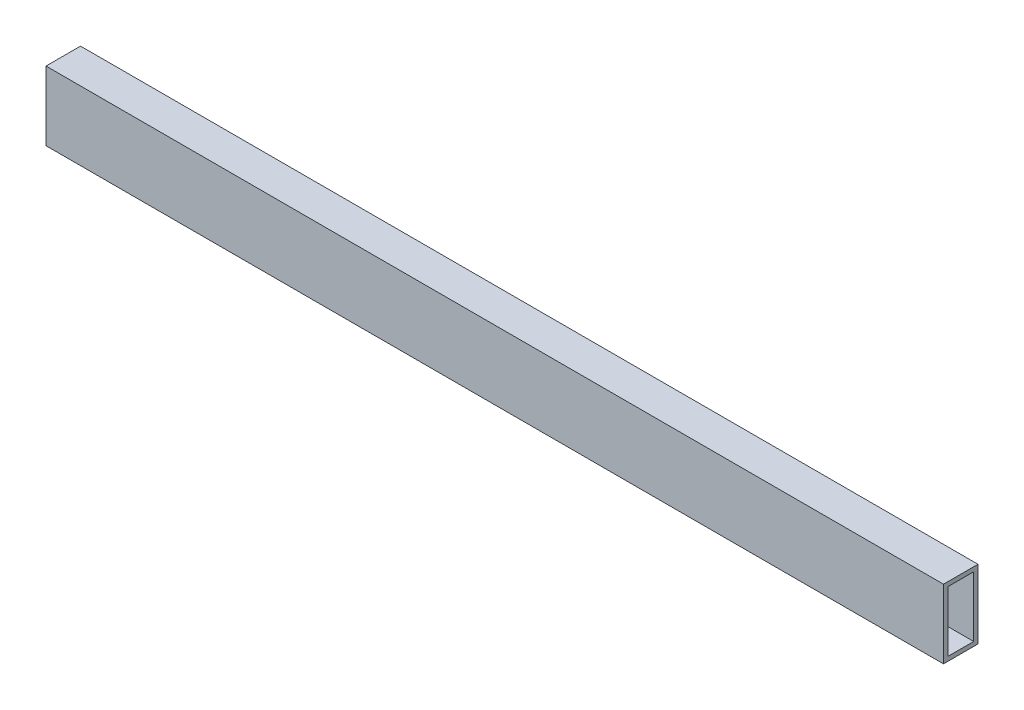
SolidWorks part; units mm, degrees
material "6061-T6 (SS)"
ref_plane "Front Plane" through (0, 0, 0) normal (0, 0, 1) x (1, 0, 0)
ref_plane "Top Plane" through (0, 0, 0) normal (0, 1, 0) x (1, 0, 0)
ref_plane "Right Plane" through (0, 0, 0) normal (1, 0, 0) x (0, 0, -1)
sketch "Sketch1" plane through (0, 0, 0) normal (1, 0, 0) x (0, 0, -1)
  line L0 (-355.6, 25.4) -> (-381, 25.4) construction
  line L1 (-381, -25.4) -> (-381, 25.4) construction
  line L2 (-355.6, -25.4) -> (-381, -25.4) construction
  line L3 (-355.6, -25.4) -> (-355.6, 25.4) construction
  line L4 (-355.6, 25.4) -> (-381, 25.4)
  line L5 (-381, -25.4) -> (-381, 25.4)
  line L6 (-355.6, -25.4) -> (-381, -25.4)
  line L7 (-355.6, -25.4) -> (-355.6, 25.4)
  line L8 (-358.775, 22.225) -> (-377.825, 22.225)
  line L9 (-377.825, -22.225) -> (-377.825, 22.225)
  line L10 (-358.775, -22.225) -> (-377.825, -22.225)
  line L11 (-358.775, -22.225) -> (-358.775, 22.225)
  dimension "D1" = 3.175
extrude "Boss-Extrude1" add sketch "Sketch1" along normal up to vertex (330.2 mm away)
ref_plane "Plane1" through (330.2, 25.4, 355.6) normal (-1, 0, 0) x (0, 0, 1)
sketch "Sketch3" plane through (0, 0, 0) normal (0, 1, 0) x (1, 0, 0)
  line L0 (266.7, -381) -> (221.678, -335.978) construction
  line L1 (266.7, -381) -> (221.678, -335.978)
  line L4 (221.678, -335.978) -> (266.7, -335.978)
  line L5 (266.7, -381) -> (266.7, 0) construction
  line L6 (266.7, -335.978) -> (266.7, -381)
extrude "Cut-Extrude2" [suppressed] cut sketch "Sketch3" against normal through all both and the other way through all
mirror "Mirror1" about plane through (0, 0, 0) normal (1, 0, 0) of "Boss-Extrude1", "Cut-Extrude2"
